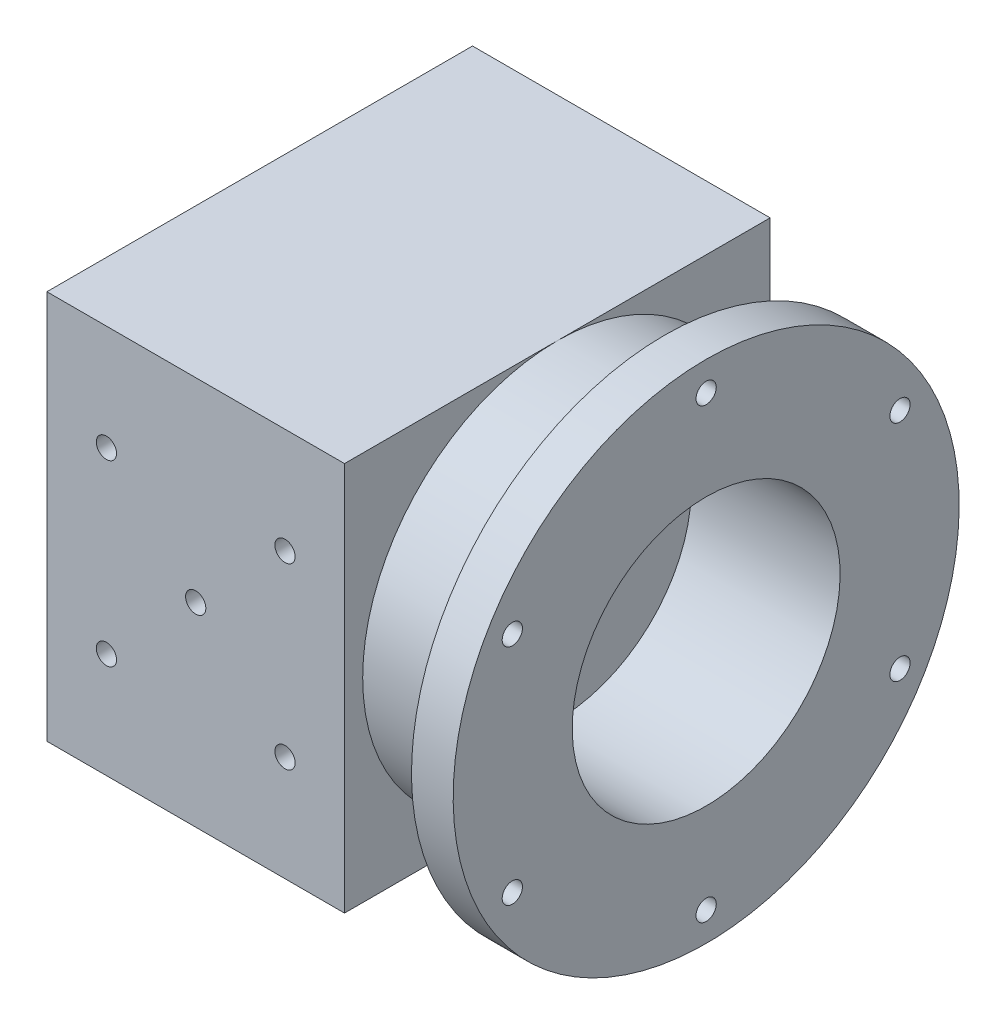
SolidWorks part; units mm, degrees
other "Elemento de detalle1"
other "Carpeta de soldadura"
other "Cordón de soldadura1"
material "7075-O (SS)"
ref_plane "Front" through (0, 0, 0) normal (0, 0, 1) x (1, 0, 0)
ref_plane "Top" through (0, 0, 0) normal (0, 1, 0) x (1, 0, 0)
ref_plane "Right" through (0, 0, 0) normal (1, 0, 0) x (0, 0, -1)
sketch "Croquis1" plane through (0, 0, 0) normal (0, 0, 1) x (1, 0, 0)
  line L0 (55, 0) -> (-55, 0) construction
  line L1 (-25, 32.7) -> (25, 32.7)
  line L2 (25, 32.7) -> (25, -32.7)
  line L3 (25, -32.7) -> (-25, -32.7)
  line L4 (0, -55) -> (0, 55) construction
  line L5 (-25, 32.7) -> (-25, -32.7)
  point P8 (25, 0)
  point P12 (0, -32.7)
  dimension "D1" = 50
  dimension "D2" = 65.4
extrude "Saliente-Extruir1" add sketch "Croquis1" along normal mid plane 71.5
sketch "Croquis2" plane through (25, 0, 0) normal (1, 0, 0) x (0, 0, -1)
  circle A0 centre (0, 0) radius 32.7
  circle A1 centre (0, 0) radius 22.5
  dimension "D1" = 65.4
  dimension "D2" = 45
extrude "Saliente-Extruir2" add sketch "Croquis2" along normal blind 25 separate body
sketch "Croquis3" plane through (50, 0, 0) normal (1, 0, 0) x (0, 0, -1)
  circle A0 centre (0, 0) radius 42.5
  circle A1 centre (0, 0) radius 32.7 construction
  circle A2 centre (0, 0) radius 32.7
  dimension "D1" = 85
extrude "Saliente-Extruir3" add sketch "Croquis3" against normal blind 7
hole_wizard "Taladro de margen para M31" positions "Croquis4" profile "Croquis5" hole size "M3" standard "Ansi Metric" end condition up to next
sketch "Croquis4" plane through (50, 0, 0) normal (1, 0, 0) x (0, 0, -1)
  line L0 (0, 42.5) -> (0, 32.7) construction
  line L1 (0, 35.97) -> (0, -35.97) construction
  circle A0 centre (0, 0) radius 32.7 construction
  circle A1 centre (0, 0) radius 42.5 construction
  point P15 (0, 37.6)
  point P22 (32.5626, 18.8)
  point P23 (32.5626, -18.8)
  point P24 (0, -37.6)
  point P25 (-32.5626, -18.8)
  point P26 (-32.5626, 18.8)
  dimension "D1" = 65.4
  dimension "D2" = 6
sketch "Croquis5" plane through (50, 18.8, 32.5626) normal (0, 1, 0) x (0, 0, -1)
  line L0 (0, 0) -> (0, 7.001)
  line L1 (0, 7.001) -> (1.7, 7.001)
  line L2 (1.7, 7.001) -> (1.7, 0)
  line L5 (1.7, 0) -> (0, 0)
  line L11 (0, -6.35) -> (0, 107.95) construction
  dimension "Diámetro de taladro hasta el siguiente" = 3.4
  dimension "Profundidad de taladro hasta el siguiente" = 7.001
sketch "Croquis9" plane through (0, 0, 0) normal (0, 0, 1) x (1, 0, 0)
  line L0 (-73, -16.1182) -> (-73, 0) construction
  line L1 (-73, 0) -> (-51.5289, 0) construction
  line L2 (-25, 32.7) -> (-25, -32.7) construction
  point P7 (0, 0)
  point P8 (0, 0)
  dimension "D1" = 48
hole_wizard "Taladro de margen para M32" positions "Croquis10" profile "Croquis12" hole size "M3" standard "Ansi Metric" end condition through all
sketch "Croquis10" plane through (0, 0, 35.75) normal (0, 0, 1) x (1, 0, 0)
  line L1 (-15, -15) -> (15, -15) construction
  line L2 (-15, -15) -> (-15, 15) construction
  line L3 (-15, 15) -> (15, 15) construction
  line L4 (15, -15) -> (15, 15) construction
  line L5 (-15, -15) -> (15, 15) construction
  line L6 (-15, 15) -> (15, -15) construction
  point P2 (15, 15)
  point P17 (-15, -15)
  point P18 (-15, 15)
  point P19 (15, -15)
  point P32 (0, 0)
  dimension "D1" = 30
sketch "Croquis12" plane through (15, 15, 35.75) normal (1, 0, 0) x (0, -1, 0)
  line L0 (0, 0) -> (0, 78.25)
  line L1 (0, 78.25) -> (1.7, 78.25)
  line L2 (1.7, 78.25) -> (1.7, 0)
  line L5 (1.7, 0) -> (0, 0)
  line L11 (0, -6.35) -> (0, 107.95) construction
  dimension "Diámetro de taladro hasta el siguiente" = 3.4
  dimension "Profundidad de taladro hasta el siguiente" = 78.25
